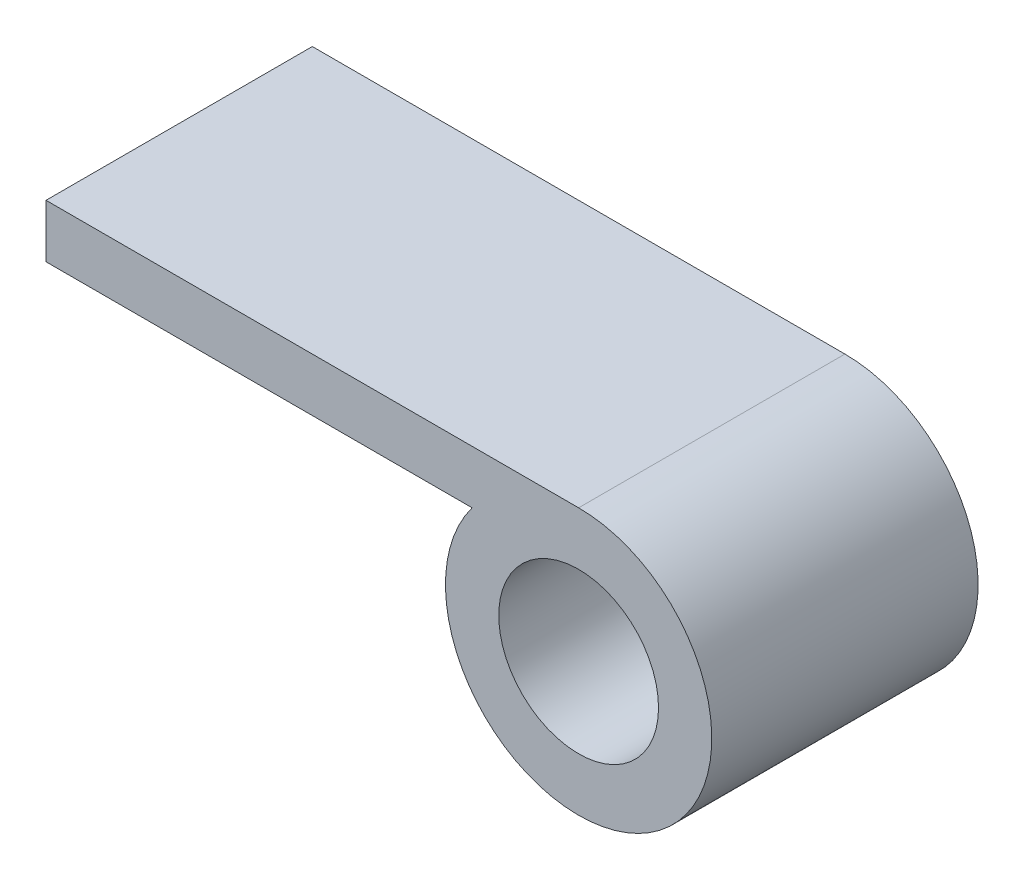
SolidWorks part; units mm, degrees
ref_plane "Front Plane" through (0, 0, 0) normal (0, 0, 1) x (1, 0, 0)
ref_plane "Top Plane" through (0, 0, 0) normal (0, 1, 0) x (1, 0, 0)
ref_plane "Right Plane" through (0, 0, 0) normal (1, 0, 0) x (0, 0, -1)
sketch "Sketch1" plane through (0, 0, 0) normal (0, 0, 1) x (1, 0, 0)
  line L0 (0, 5) -> (-20, 5)
  line L1 (-20, 5) -> (-20, 3)
  line L2 (-20, 3) -> (-4, 3)
  circle A0 centre (0, 0) radius 3
  arc A1 (-4, 3) -> (0, 5) centre (0, 0) ccw
  dimension "D1" = 6
  dimension "D2" = 5
  dimension "D3" = 20
extrude "Boss-Extrude1" add sketch "Sketch1" along normal blind 10
